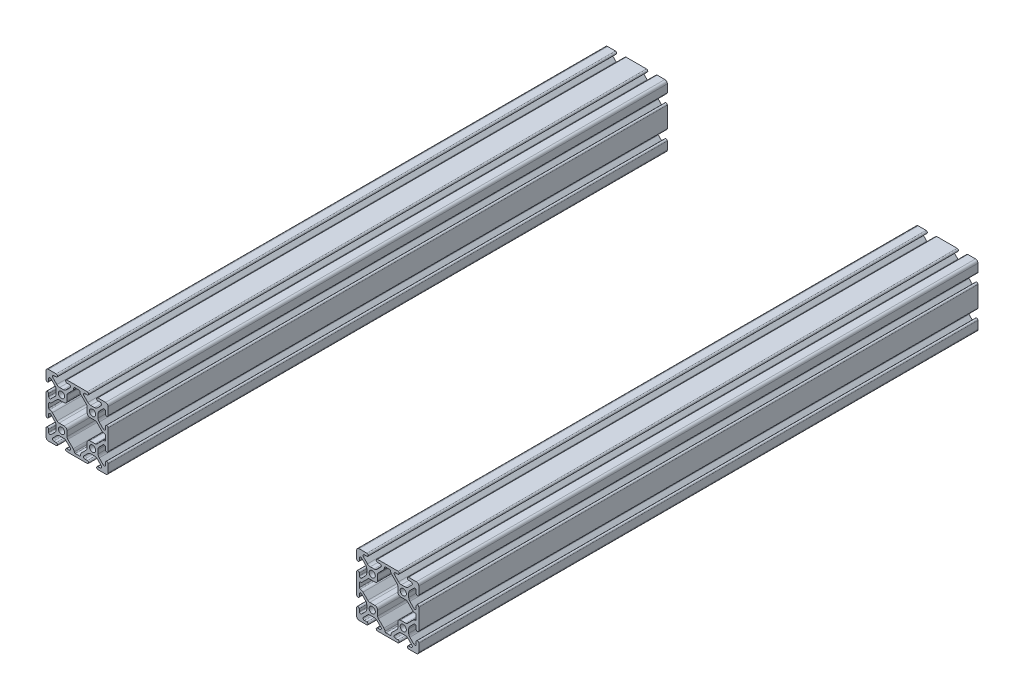
SolidWorks part; units mm, degrees
ref_plane "Front Plane" through (0, 0, 0) normal (0, 0, 1) x (1, 0, 0)
ref_plane "Top Plane" through (0, 0, 0) normal (0, 1, 0) x (1, 0, 0)
ref_plane "Right Plane" through (0, 0, 0) normal (1, 0, 0) x (0, 0, -1)
sketch3d "3DSketch1"
  line L0 (-125, -70, 0) -> (-125, 70, 0) construction
  line L1 (-140, -70, 0) -> (140, -70, 0) construction
  line L2 (140, 70, 0) -> (-140, 70, 0) construction
  line L3 (-125, 0, 0) -> (-125, 0, 450)
  line L4 (125, -70, 0) -> (125, 70, 0) construction
  line L6 (125, 0, 0) -> (125, 0, 450)
  line L7 (-125, 0, 0) -> (0, 0, 0) construction
  line L8 (0, 0, 0) -> (125, 0, 0) construction
  dimension "D1" = 250
  dimension "D4" = 450
other "25 series extrusions 25-5050(1)"
ref_plane "Plane1" through (-125, 0, 0) normal (0, 0, 1) x (0, 1, 0)
sketch "Sketch1" plane through (-125, 0, 0) normal (0, 0, 1) x (0, 1, 0)
  line L0 (1.94, -22.8664) -> (-1.461, -22.8664)
  line L1 (-3.1194, -20.3719) -> (-7.4717, -16.0197)
  line L2 (-8.1189, -14.4571) -> (-8.1189, -10.3287)
  line L3 (-10.3287, -8.1189) -> (-14.4571, -8.1189)
  line L4 (-16.0197, -7.4717) -> (-19.8593, -3.632)
  line L5 (-22.8664, -1.94) -> (-22.8664, 1.461)
  line L6 (-20.3719, 3.1194) -> (-16.0197, 7.4717)
  line L7 (-14.4571, 8.1189) -> (-10.3287, 8.1189)
  line L8 (-8.1189, 10.3287) -> (-8.1189, 14.4571)
  line L9 (-7.4717, 16.0197) -> (-3.632, 19.8593)
  line L10 (-1.94, 22.8664) -> (1.461, 22.8664)
  line L11 (3.1194, 20.3719) -> (7.4717, 16.0197)
  line L12 (8.1189, 14.4571) -> (8.1189, 10.3287)
  line L13 (10.3287, 8.1189) -> (14.4571, 8.1189)
  line L14 (16.0197, 7.4717) -> (19.8593, 3.632)
  line L15 (22.8664, 1.94) -> (22.8664, -1.461)
  line L16 (20.3719, -3.1194) -> (16.0197, -7.4717)
  line L17 (14.4571, -8.1189) -> (10.3287, -8.1189)
  line L18 (8.1189, -10.3287) -> (8.1189, -14.4571)
  line L19 (7.4717, -16.0197) -> (3.632, -19.8593)
  line L20 (16.815, -25) -> (23, -25)
  line L21 (25, -23) -> (25, -16.815)
  line L22 (22.87, -16.815) -> (22.87, -18.7728)
  line L23 (21.0396, -19.531) -> (17.811, -16.3024)
  line L24 (16.8811, -14.0573) -> (16.8811, -10.9427)
  line L25 (17.811, -8.6976) -> (21.0396, -5.469)
  line L26 (22.87, -6.2272) -> (22.87, -8.185)
  line L27 (25, -8.185) -> (25, 8.185)
  line L28 (22.87, 8.185) -> (22.87, 6.2272)
  line L29 (21.0396, 5.469) -> (17.811, 8.6976)
  line L30 (16.8811, 10.9427) -> (16.8811, 14.0573)
  line L31 (17.811, 16.3024) -> (21.0396, 19.531)
  line L32 (22.87, 18.7728) -> (22.87, 16.815)
  line L33 (25, 16.815) -> (25, 23)
  line L34 (23, 25) -> (16.815, 25)
  line L35 (16.815, 22.87) -> (18.7728, 22.87)
  line L36 (19.531, 21.0396) -> (16.3024, 17.811)
  line L37 (14.0573, 16.8811) -> (10.9427, 16.8811)
  line L38 (8.6976, 17.811) -> (5.469, 21.0396)
  line L39 (6.2272, 22.87) -> (8.185, 22.87)
  line L40 (8.185, 25) -> (-8.185, 25)
  line L41 (-8.185, 22.87) -> (-6.2272, 22.87)
  line L42 (-5.469, 21.0396) -> (-8.6976, 17.811)
  line L43 (-10.9427, 16.8811) -> (-14.0573, 16.8811)
  line L44 (-16.3024, 17.811) -> (-19.531, 21.0396)
  line L45 (-18.7728, 22.87) -> (-16.815, 22.87)
  line L46 (-16.815, 25) -> (-23, 25)
  line L47 (-25, 23) -> (-25, 16.815)
  line L48 (-22.87, 16.815) -> (-22.87, 18.7728)
  line L49 (-21.0396, 19.531) -> (-17.811, 16.3024)
  line L50 (-16.8811, 14.0573) -> (-16.8811, 10.9427)
  line L51 (-17.811, 8.6976) -> (-21.0396, 5.469)
  line L52 (-22.87, 6.2272) -> (-22.87, 8.185)
  line L53 (-25, 8.185) -> (-25, -8.185)
  line L54 (-22.87, -8.185) -> (-22.87, -6.2272)
  line L55 (-21.0396, -5.469) -> (-17.811, -8.6976)
  line L56 (-16.8811, -10.9427) -> (-16.8811, -14.0573)
  line L57 (-17.811, -16.3024) -> (-21.0396, -19.531)
  line L58 (-22.87, -18.7728) -> (-22.87, -16.815)
  line L59 (-25, -16.815) -> (-25, -23)
  line L60 (-23, -25) -> (-16.815, -25)
  line L61 (-16.815, -22.87) -> (-18.7728, -22.87)
  line L62 (-19.531, -21.0396) -> (-16.3024, -17.811)
  line L63 (-14.0573, -16.8811) -> (-10.9427, -16.8811)
  line L64 (-8.6976, -17.811) -> (-5.469, -21.0396)
  line L65 (-6.2272, -22.87) -> (-8.185, -22.87)
  line L66 (-8.185, -25) -> (8.185, -25)
  line L67 (8.185, -22.87) -> (6.2272, -22.87)
  line L68 (5.469, -21.0396) -> (8.6976, -17.811)
  line L69 (10.9427, -16.8811) -> (14.0573, -16.8811)
  line L70 (16.3024, -17.811) -> (19.531, -21.0396)
  line L71 (18.7728, -22.87) -> (16.815, -22.87)
  circle A0 centre (12.5, 12.5) radius 2.5
  circle A1 centre (-12.5, -12.5) radius 2.5
  circle A2 centre (12.5, -12.5) radius 2.5
  circle A3 centre (-12.5, 12.5) radius 2.5
  arc A4 (1.94, -22.8664) -> (2.702, -22.1044) centre (1.94, -22.1044) ccw
  arc A5 (-2.2165, -22.2036) -> (-1.461, -22.8664) centre (-1.461, -22.1044) ccw
  arc A6 (-2.2165, -22.2036) -> (-3.1194, -20.3719) centre (-5.3645, -22.617) ccw
  arc A7 (-8.1189, -14.4571) -> (-7.4717, -16.0197) centre (-5.9091, -14.4571) ccw
  arc A8 (-8.1189, -10.3287) -> (-10.3287, -8.1189) centre (-10.3287, -10.3287) ccw
  arc A9 (-16.0197, -7.4717) -> (-14.4571, -8.1189) centre (-14.4571, -5.9091) ccw
  arc A10 (-19.8593, -3.632) -> (-22.1044, -2.702) centre (-22.1044, -5.877) ccw
  arc A11 (-22.8664, -1.94) -> (-22.1044, -2.702) centre (-22.1044, -1.94) ccw
  arc A12 (-22.2036, 2.2165) -> (-22.8664, 1.461) centre (-22.1044, 1.461) ccw
  arc A13 (-22.2036, 2.2165) -> (-20.3719, 3.1194) centre (-22.617, 5.3645) ccw
  arc A14 (-14.4571, 8.1189) -> (-16.0197, 7.4717) centre (-14.4571, 5.9091) ccw
  arc A15 (-10.3287, 8.1189) -> (-8.1189, 10.3287) centre (-10.3287, 10.3287) ccw
  arc A16 (-7.4717, 16.0197) -> (-8.1189, 14.4571) centre (-5.9091, 14.4571) ccw
  arc A17 (-3.632, 19.8593) -> (-2.702, 22.1044) centre (-5.877, 22.1044) ccw
  arc A18 (-1.94, 22.8664) -> (-2.702, 22.1044) centre (-1.94, 22.1044) ccw
  arc A19 (2.2165, 22.2036) -> (1.461, 22.8664) centre (1.461, 22.1044) ccw
  arc A20 (2.2165, 22.2036) -> (3.1194, 20.3719) centre (5.3645, 22.617) ccw
  arc A21 (8.1189, 14.4571) -> (7.4717, 16.0197) centre (5.9091, 14.4571) ccw
  arc A22 (8.1189, 10.3287) -> (10.3287, 8.1189) centre (10.3287, 10.3287) ccw
  arc A23 (16.0197, 7.4717) -> (14.4571, 8.1189) centre (14.4571, 5.9091) ccw
  arc A24 (19.8593, 3.632) -> (22.1044, 2.702) centre (22.1044, 5.877) ccw
  arc A25 (22.8664, 1.94) -> (22.1044, 2.702) centre (22.1044, 1.94) ccw
  arc A26 (22.2036, -2.2165) -> (22.8664, -1.461) centre (22.1044, -1.461) ccw
  arc A27 (22.2036, -2.2165) -> (20.3719, -3.1194) centre (22.617, -5.3645) ccw
  arc A28 (14.4571, -8.1189) -> (16.0197, -7.4717) centre (14.4571, -5.9091) ccw
  arc A29 (10.3287, -8.1189) -> (8.1189, -10.3287) centre (10.3287, -10.3287) ccw
  arc A30 (7.4717, -16.0197) -> (8.1189, -14.4571) centre (5.9091, -14.4571) ccw
  arc A31 (3.632, -19.8593) -> (2.702, -22.1044) centre (5.877, -22.1044) ccw
  arc A32 (23, -25) -> (25, -23) centre (23, -23) ccw
  arc A33 (25, -16.815) -> (22.87, -16.815) centre (23.935, -16.815) ccw
  arc A34 (21.0396, -19.531) -> (22.87, -18.7728) centre (21.7978, -18.7728) ccw
  arc A35 (16.8811, -14.0573) -> (17.811, -16.3024) centre (20.0561, -14.0573) ccw
  arc A36 (17.811, -8.6976) -> (16.8811, -10.9427) centre (20.0561, -10.9427) ccw
  arc A37 (22.87, -6.2272) -> (21.0396, -5.469) centre (21.7978, -6.2272) ccw
  arc A38 (22.87, -8.185) -> (25, -8.185) centre (23.935, -8.185) ccw
  arc A39 (25, 8.185) -> (22.87, 8.185) centre (23.935, 8.185) ccw
  arc A40 (21.0396, 5.469) -> (22.87, 6.2272) centre (21.7978, 6.2272) ccw
  arc A41 (16.8811, 10.9427) -> (17.811, 8.6976) centre (20.0561, 10.9427) ccw
  arc A42 (17.811, 16.3024) -> (16.8811, 14.0573) centre (20.0561, 14.0573) ccw
  arc A43 (22.87, 18.7728) -> (21.0396, 19.531) centre (21.7978, 18.7728) ccw
  arc A44 (22.87, 16.815) -> (25, 16.815) centre (23.935, 16.815) ccw
  arc A45 (25, 23) -> (23, 25) centre (23, 23) ccw
  arc A46 (16.815, 25) -> (16.815, 22.87) centre (16.815, 23.935) ccw
  arc A47 (19.531, 21.0396) -> (18.7728, 22.87) centre (18.7728, 21.7978) ccw
  arc A48 (14.0573, 16.8811) -> (16.3024, 17.811) centre (14.0573, 20.0561) ccw
  arc A49 (8.6976, 17.811) -> (10.9427, 16.8811) centre (10.9427, 20.0561) ccw
  arc A50 (6.2272, 22.87) -> (5.469, 21.0396) centre (6.2272, 21.7978) ccw
  arc A51 (8.185, 22.87) -> (8.185, 25) centre (8.185, 23.935) ccw
  arc A52 (-8.185, 25) -> (-8.185, 22.87) centre (-8.185, 23.935) ccw
  arc A53 (-5.469, 21.0396) -> (-6.2272, 22.87) centre (-6.2272, 21.7978) ccw
  arc A54 (-10.9427, 16.8811) -> (-8.6976, 17.811) centre (-10.9427, 20.0561) ccw
  arc A55 (-16.3024, 17.811) -> (-14.0573, 16.8811) centre (-14.0573, 20.0561) ccw
  arc A56 (-18.7728, 22.87) -> (-19.531, 21.0396) centre (-18.7728, 21.7978) ccw
  arc A57 (-16.815, 22.87) -> (-16.815, 25) centre (-16.815, 23.935) ccw
  arc A58 (-23, 25) -> (-25, 23) centre (-23, 23) ccw
  arc A59 (-25, 16.815) -> (-22.87, 16.815) centre (-23.935, 16.815) ccw
  arc A60 (-21.0396, 19.531) -> (-22.87, 18.7728) centre (-21.7978, 18.7728) ccw
  arc A61 (-16.8811, 14.0573) -> (-17.811, 16.3024) centre (-20.0561, 14.0573) ccw
  arc A62 (-17.811, 8.6976) -> (-16.8811, 10.9427) centre (-20.0561, 10.9427) ccw
  arc A63 (-22.87, 6.2272) -> (-21.0396, 5.469) centre (-21.7978, 6.2272) ccw
  arc A64 (-22.87, 8.185) -> (-25, 8.185) centre (-23.935, 8.185) ccw
  arc A65 (-25, -8.185) -> (-22.87, -8.185) centre (-23.935, -8.185) ccw
  arc A66 (-21.0396, -5.469) -> (-22.87, -6.2272) centre (-21.7978, -6.2272) ccw
  arc A67 (-16.8811, -10.9427) -> (-17.811, -8.6976) centre (-20.0561, -10.9427) ccw
  arc A68 (-17.811, -16.3024) -> (-16.8811, -14.0573) centre (-20.0561, -14.0573) ccw
  arc A69 (-22.87, -18.7728) -> (-21.0396, -19.531) centre (-21.7978, -18.7728) ccw
  arc A70 (-22.87, -16.815) -> (-25, -16.815) centre (-23.935, -16.815) ccw
  arc A71 (-25, -23) -> (-23, -25) centre (-23, -23) ccw
  arc A72 (-16.815, -25) -> (-16.815, -22.87) centre (-16.815, -23.935) ccw
  arc A73 (-19.531, -21.0396) -> (-18.7728, -22.87) centre (-18.7728, -21.7978) ccw
  arc A74 (-14.0573, -16.8811) -> (-16.3024, -17.811) centre (-14.0573, -20.0561) ccw
  arc A75 (-8.6976, -17.811) -> (-10.9427, -16.8811) centre (-10.9427, -20.0561) ccw
  arc A76 (-6.2272, -22.87) -> (-5.469, -21.0396) centre (-6.2272, -21.7978) ccw
  arc A77 (-8.185, -22.87) -> (-8.185, -25) centre (-8.185, -23.935) ccw
  arc A78 (8.185, -25) -> (8.185, -22.87) centre (8.185, -23.935) ccw
  arc A79 (5.469, -21.0396) -> (6.2272, -22.87) centre (6.2272, -21.7978) ccw
  arc A80 (10.9427, -16.8811) -> (8.6976, -17.811) centre (10.9427, -20.0561) ccw
  arc A81 (16.3024, -17.811) -> (14.0573, -16.8811) centre (14.0573, -20.0561) ccw
  arc A82 (18.7728, -22.87) -> (19.531, -21.0396) centre (18.7728, -21.7978) ccw
  arc A83 (16.815, -22.87) -> (16.815, -25) centre (16.815, -23.935) ccw
  point P0 (0, 0)
